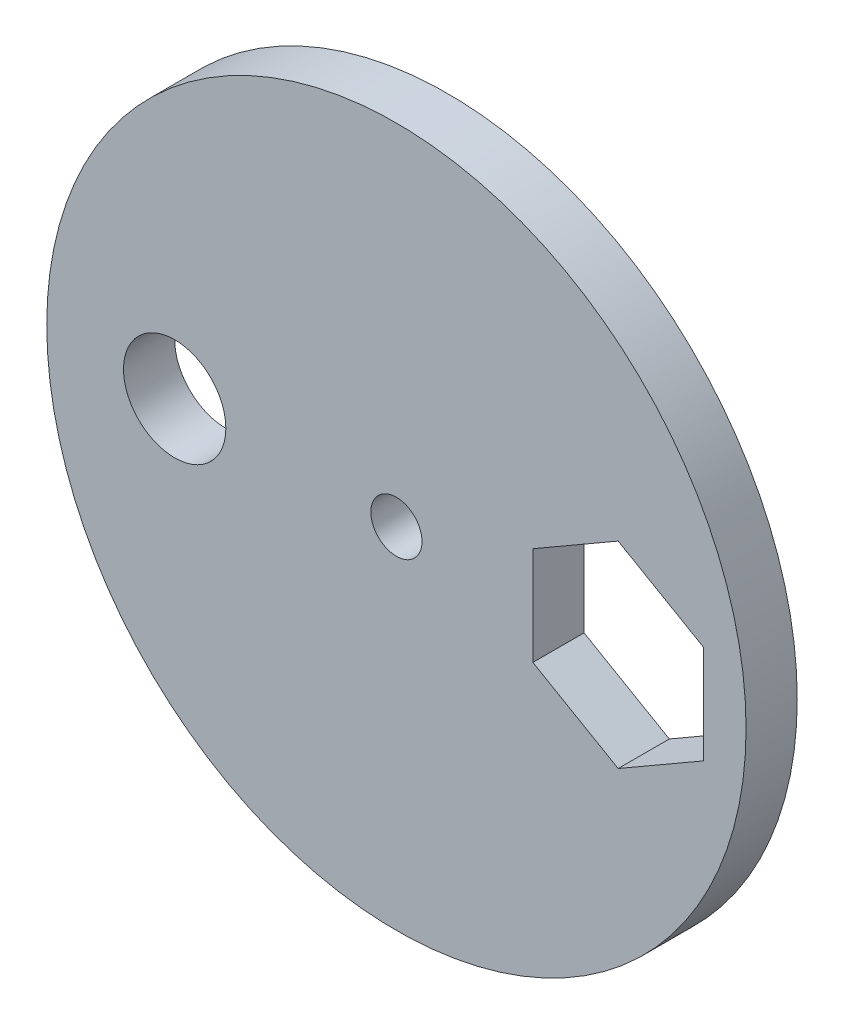
SolidWorks part; units mm, degrees
material "Acrylic (Medium-high impact)"
ref_plane "Front Plane" through (0, 0, 0) normal (0, 0, 1) x (1, 0, 0)
ref_plane "Top Plane" through (0, 0, 0) normal (0, 1, 0) x (1, 0, 0)
ref_plane "Right Plane" through (0, 0, 0) normal (1, 0, 0) x (0, 0, -1)
sketch "Sketch1" plane through (0, 0, 0) normal (0, 0, 1) x (1, 0, 0)
  line L0 (0, 20.5) -> (0, -20.5) construction
  line L2 (18, 2.8868) -> (13, 5.7735)
  line L3 (13, 5.7735) -> (8, 2.8868)
  line L4 (8, 2.8868) -> (8, -2.8868)
  line L5 (8, -2.8868) -> (13, -5.7735)
  line L6 (13, -5.7735) -> (18, -2.8868)
  line L7 (18, -2.8868) -> (18, 2.8868)
  circle A0 centre (0, 0) radius 20.5
  circle A2 centre (-13, 0) radius 3
  circle A3 centre (0, 0) radius 1.5
  circle A4 centre (13, 0) radius 5 construction
  dimension "D1" = 41
  dimension "D2" = 13
  dimension "D3" = 6
  dimension "D4" = 3
  dimension "D5" = 10
extrude "Boss-Extrude1" add sketch "Sketch1" along normal blind 3
equation "\"D1@Sketch1\"=40.8+\"cut_free@Parameters@FabricationParameters.sldprt\""
